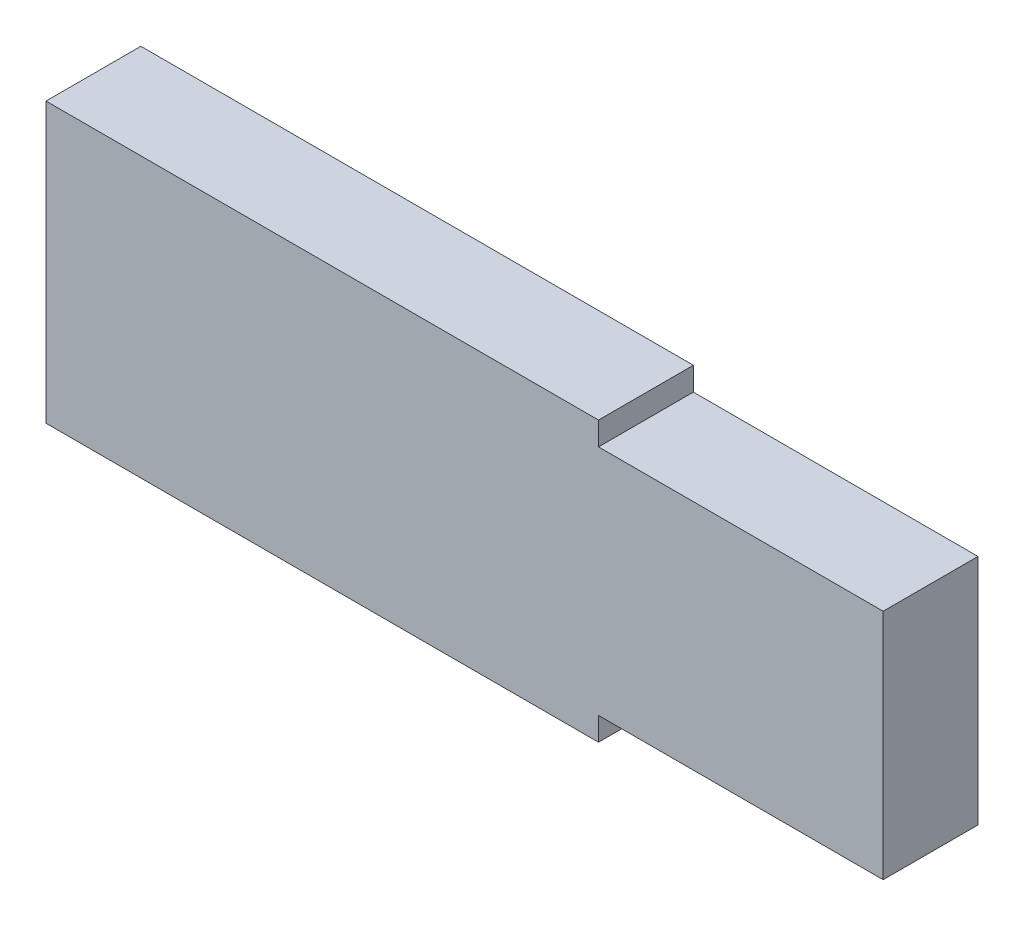
SolidWorks part; units mm, degrees
ref_plane "Front Plane" through (0, 0, 0) normal (0, 0, 1) x (1, 0, 0)
ref_plane "Top Plane" through (0, 0, 0) normal (0, 1, 0) x (1, 0, 0)
ref_plane "Right Plane" through (0, 0, 0) normal (1, 0, 0) x (0, 0, -1)
sketch "Sketch1" plane through (0, 0, 0) normal (0, 0, 1) x (1, 0, 0)
  line L1 (80, -7.5) -> (50.3, -7.5)
  line L2 (80, -7.5) -> (80, -6.25)
  line L3 (80, 7.5) -> (50.3, 7.5)
  line L5 (80, -7.5) -> (50.3, -4.7156) construction
  line L6 (80, 7.5) -> (50.3, 4.7156) construction
  line L11 (80, 6.25) -> (95.3, 6.25)
  line L13 (80, -6.25) -> (95.3, -6.25)
  line L14 (95.3, 6.25) -> (95.3, -6.25)
  line L15 (80, 6.25) -> (80, 7.5)
  line L16 (50.3, 7.5) -> (50.3, -7.5)
  point P0 (0, 0)
  point P15 (95.3, 0)
  dimension "D3" = 15.3
  dimension "D4" = 12.5
  dimension "D6" = 15
  dimension "D7" = 45
extrude "Boss-Extrude2" add sketch "Sketch1" along normal blind 5.1
